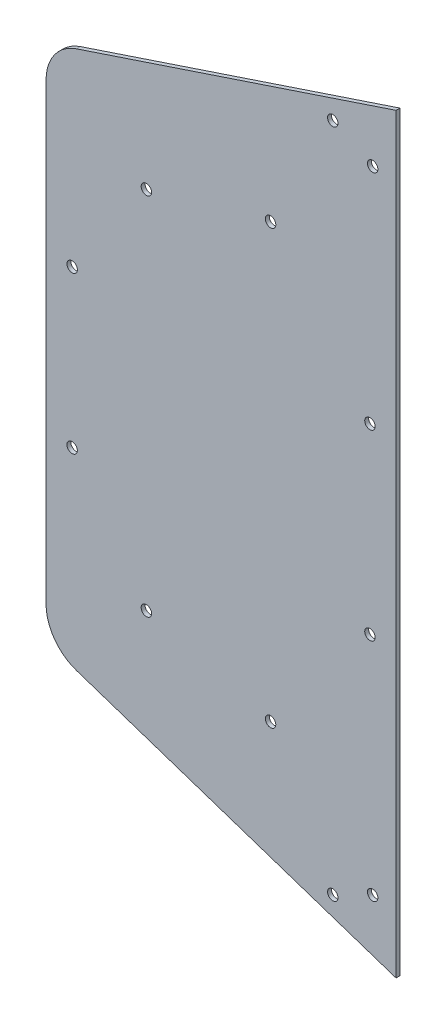
SolidWorks part; units mm, degrees
ref_plane "Front Plane" through (0, 0, 0) normal (1, 0, 0) x (0, 1, 0)
ref_plane "Top Plane" through (0, 0, 0) normal (0, 0, 1) x (0, 1, 0)
ref_plane "Right Plane" through (0, 0, 0) normal (0, 1, 0) x (-1, 0, 0)
sketch "Sketch1" plane through (0, 0, 0) normal (0, 0, 1) x (0, 1, 0)
  line L0 (-310, 0) -> (310, 0) construction
  line L1 (0, 0) -> (0, 300) construction
  line L2 (173.962, 300) -> (-173.962, 300) construction
  line L3 (-221.3962, 265.8114) -> (-310, 0) construction
  line L4 (221.3962, 265.8114) -> (310, 0) construction
  line L5 (206.3359, 260.7913) -> (287.9746, 15.875)
  line L6 (173.962, 284.125) -> (-173.962, 284.125)
  line L7 (-206.3359, 260.7913) -> (-287.9746, 15.875)
  line L8 (-310, 15.875) -> (310, 15.875)
  line L9 (-206.3359, 260.7913) -> (-294.9397, -5.0201) construction
  line L10 (206.3359, 260.7913) -> (294.9397, -5.0201) construction
  line L11 (-287.9746, 15.875) -> (-293.2663, 0) construction
  line L12 (287.9746, 15.875) -> (293.2663, 0) construction
  line L13 (0, 300) -> (-97.75, 300) construction
  line L14 (-221.3962, 265.8114) -> (-245.9987, 192.0038) construction
  line L15 (-97.75, 300) -> (-232.5827, 165.1708) construction
  line L16 (-245.9987, 192.0038) -> (-150, 0) construction
  line L17 (245.9987, 192.0038) -> (150, 0) construction
  line L18 (97.75, 300) -> (232.5827, 165.1708) construction
  line L19 (0, 284.125) -> (-60, 284.125)
  line L20 (-60, 284.125) -> (-60, 264.125) construction
  line L21 (-86.5248, 288.7745) -> (-221.3575, 153.9454) construction
  line L22 (-91.1745, 284.125) -> (-221.3575, 153.9454) construction
  line L23 (-136.0763, 284.125) -> (-229.7975, 190.4063) construction
  line L24 (-221.3575, 153.9454) -> (-225.0993, 150.2036) construction
  line L25 (-165.1663, 232.5854) -> (-153.9412, 221.36) construction
  line L26 (-153.9412, 221.36) -> (-139.7992, 207.2176) construction
  line L27 (-243.0582, 150.6241) -> (-175.6859, 15.875) construction
  line L28 (-228.859, 193.2218) -> (-140.1886, 15.875) construction
  line L29 (-260.1979, 184.9045) -> (-164.1991, -7.0993) construction
  line L30 (-231.7996, 199.1032) -> (-135.8009, 7.0993) construction
  line L31 (-197.9994, 96.0019) -> (-183.8002, 103.1012) construction
  line L32 (-183.8002, 103.1012) -> (-165.9116, 112.0453) construction
  line L33 (0, 15.875) -> (-70, 15.875) construction
  line L34 (-70, 15.875) -> (-70, 35.875) construction
  line L35 (-287.9746, 15.875) -> (-232.9746, 15.875)
  line L36 (-287.9746, 15.875) -> (-265.8387, 82.2828) construction
  line L37 (-265.8387, 82.2828) -> (-232.9746, 15.875) construction
  line L38 (-268.533, 74.1998) -> (-239.6691, 15.875) construction
  line L39 (-260.4611, 84.9441) -> (-227.5971, 18.5362) construction
  line L40 (-271.2162, 79.6216) -> (-238.3521, 13.2138) construction
  line L41 (-227.5971, 18.5362) -> (-226.2801, 15.875) construction
  line L42 (-260.4611, 84.9441) -> (-263.1443, 90.3659) construction
  line L43 (-265.8387, 82.2828) -> (-256.9679, 64.3577) construction
  line L44 (-232.9746, 15.875) -> (-241.8454, 33.8001) construction
  arc A0 (-173.962, 300) -> (-221.3962, 265.8114) centre (-173.962, 250) ccw construction
  arc A1 (221.3962, 265.8114) -> (173.962, 300) centre (173.962, 250) ccw construction
  arc A2 (206.3359, 260.7913) -> (173.962, 284.125) centre (173.962, 250) ccw
  arc A3 (-173.962, 284.125) -> (-206.3359, 260.7913) centre (-173.962, 250) ccw
  circle A4 centre (-60, 264.125) radius 4
  circle A5 centre (-139.7992, 207.2176) radius 4
  circle A6 centre (-165.9116, 112.0453) radius 4
  circle A7 centre (-70, 35.875) radius 4
  circle A8 centre (70, 35.875) radius 4
  circle A9 centre (165.9116, 112.0453) radius 4
  circle A10 centre (139.7992, 207.2176) radius 4
  circle A11 centre (60, 264.125) radius 4
  circle A12 centre (-256.9679, 64.3577) radius 4
  circle A13 centre (-241.8454, 33.8001) radius 4
  circle A14 centre (241.8454, 33.8001) radius 4
  circle A15 centre (256.9679, 64.3577) radius 4
  point P4 (0, 0)
  point P10 (0, 300)
  point P12 (-210, 300)
  point P15 (210, 300)
  dimension "D4" = 50
  dimension "D5" = 50
  dimension "D13" = 8
  dimension "D17" = 8
  dimension "D21" = 8
  dimension "D24" = 8
  dimension "D29" = 8
  dimension "D30" = 8
  dimension "D1" = 620
  dimension "D2" = 300
  dimension "D3" = 420
  dimension "D8" = 97.75
  dimension "D9" = 77.8
  dimension "D10" = 150
  dimension "D11" = 30
  dimension "D12" = 20
  dimension "D14" = 60
  dimension "D15" = 20
  dimension "D20" = 20
  dimension "D22" = 20
  dimension "D23" = 70
  dimension "D25" = 55
  dimension "D26" = 70
  dimension "D27" = 20
  dimension "D28" = 20
  dimension "D31" = 6
  dimension "D32" = 6
  dimension "D33" = 4.26
  dimension "D34" = 15.875
  dimension "D6" = 15.875
  dimension "D7" = 15.875
  dimension "D16" = 15.875
  dimension "D18" = 15.875
  dimension "D19" = 15.875
extrude "Boss-Extrude2" add sketch "Sketch1" along normal blind 3 contours L6 A3 L7 L0 L5 A2
sketch "Sketch2" plane through (0, 0, 3) normal (0, 0, 1) x (1, 0, 0)
  line L0 (-15.875, 0) -> (-284.125, 0) construction
  line L1 (-284.125, 173.962) -> (-284.125, -173.962) construction
  line L2 (-15.875, 100) -> (-284.125, 100) construction
  line L3 (-15.875, -100) -> (-284.125, -100) construction
  line L4 (-15.875, 0) -> (-95.875, 0) construction
  line L5 (-15.875, -287.9746) -> (-15.875, 287.9746) construction
  line L6 (-15.875, -287.9746) -> (-15.875, 287.9746)
  line L7 (-95.875, 0) -> (-95.875, 10) construction
  line L8 (-15.875, 100) -> (-95.875, 100) construction
  line L9 (0, 100) -> (-284.125, 100) construction
  line L10 (0, 0) -> (-284.125, 0) construction
  line L11 (0, -100) -> (-284.125, -100) construction
  line L12 (-15.875, -100) -> (-95.875, -100) construction
  line L13 (-95.875, 85) -> (-95.875, 115) construction
  line L14 (-95.875, -100) -> (-95.875, -110) construction
  point P12 (-15.875, 0)
  point P13 (-95.875, 0)
  point P18 (-95.875, 10)
  point P24 (-95.875, 100)
  dimension "D3" = 80
  dimension "D4" = 30
  dimension "D5" = 10
  dimension "D6" = 80
  dimension "D7" = 80
  dimension "D8" = 10
  dimension "D1" = 100
  dimension "D2" = 100
